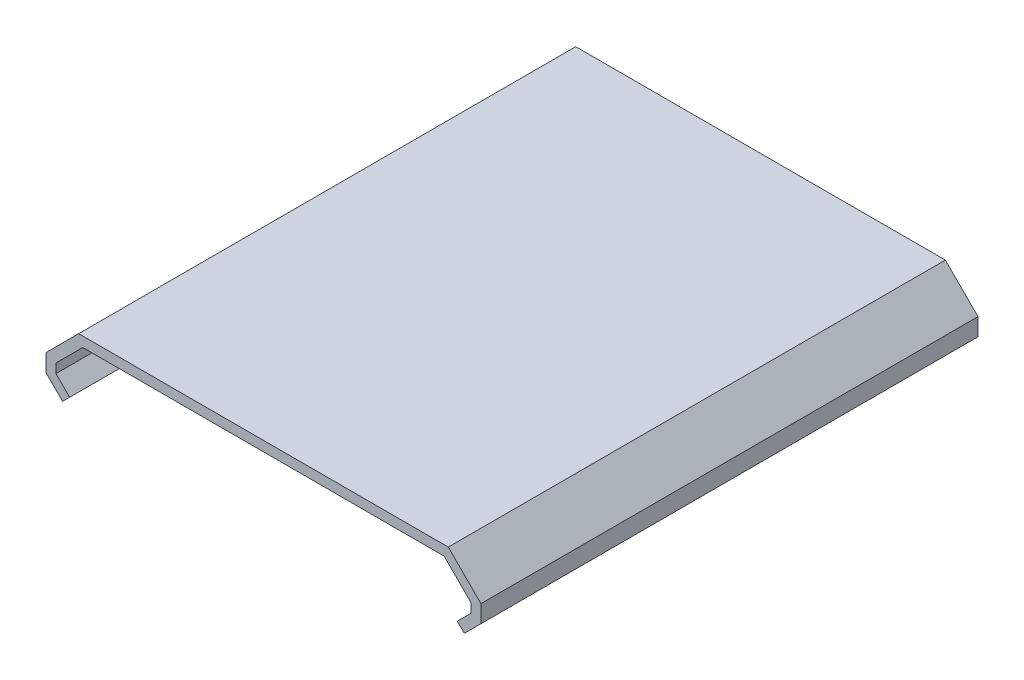
SolidWorks part; units mm, degrees
ref_plane "前视基准面" through (0, 0, 0) normal (0, 0, 1) x (1, 0, 0)
ref_plane "上视基准面" through (0, 0, 0) normal (0, 1, 0) x (1, 0, 0)
ref_plane "右视基准面" through (0, 0, 0) normal (1, 0, 0) x (0, 0, -1)
other "Configuration Table"
sketch "草图1" plane through (0, 0, 0) normal (0, 0, 1) x (1, 0, 0)
  line L0 (0, 0) -> (0, 52) construction
  line L1 (72.7071, 52) -> (-72.7071, 52)
  line L2 (-72.7071, 52) -> (-83.5, 41.2071)
  line L3 (-83.5, 41.2071) -> (-83.5, 37.5)
  line L4 (-83.5, 37.5) -> (-78, 32)
  line L5 (-83, 37) -> (-77, 31) construction
  line L6 (-77, 47) -> (-83, 41) construction
  line L7 (-83, 41) -> (-83, 37) construction
  line L8 (77, 47) -> (74, 47) construction
  line L9 (-77, 31) -> (-77, 0) construction
  line L10 (83.5, 37.5) -> (78, 32)
  line L11 (83.5, 41.2071) -> (83.5, 37.5)
  line L12 (72.7071, 52) -> (83.5, 41.2071)
  point P17 (0, 0)
  dimension "D1" = 0.5
  dimension "D2" = 0.5
  dimension "D3" = 5
  dimension "D4" = 1
extrude "拉伸-薄壁1" add sketch "草图1" against normal blind 200 thin
sketch "草图2" plane through (0, 0, -200) normal (0, 0, -1) x (-1, 0, 0)
  line L0 (-7.9899, 52) -> (3, 52)
  line L1 (72.7071, 52) -> (-72.7071, 52) construction
  line L2 (3, 52) -> (3, 41.0101)
  line L3 (3, 41.0101) -> (-7.9899, 52)
  line L5 (3, 39.5958) -> (3, 3) construction
  line L6 (-4.4042, 47) -> (3, 39.5958) construction
  dimension "D1" = 1
extrude "凸台-拉伸1" add sketch "草图2" against normal blind 17
